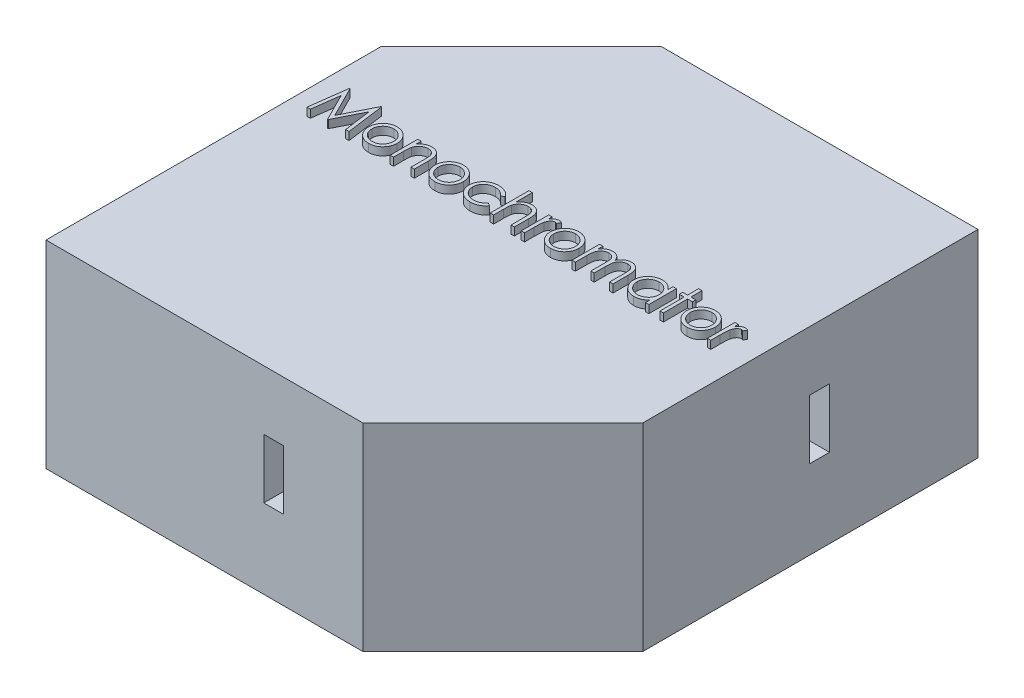
SolidWorks part; units mm, degrees
ref_plane "Front Plane" through (0, 0, 0) normal (0, 0, 1) x (1, 0, 0)
ref_plane "Top Plane" through (0, 0, 0) normal (0, 1, 0) x (1, 0, 0)
ref_plane "Right Plane" through (0, 0, 0) normal (1, 0, 0) x (0, 0, -1)
sketch "Sketch2" plane through (0, 0, 0) normal (0, 1, 0) x (1, 0, 0)
  line L0 (0, 0) -> (80, 0)
  line L1 (80, 0) -> (115.3553, 35.3553)
  line L2 (115.3553, 35.3553) -> (115.3553, 120)
  line L3 (115.3553, 120) -> (35.3553, 120)
  line L4 (35.3553, 120) -> (0, 84.6447)
  line L5 (0, 84.6447) -> (0, 0)
  line L6 (5, 5) -> (77.9289, 5)
  line L7 (77.9289, 5) -> (110.3553, 37.4264)
  line L8 (110.3553, 37.4264) -> (110.3553, 115)
  line L9 (110.3553, 115) -> (37.4264, 115)
  line L10 (37.4264, 115) -> (5, 82.5736)
  line L11 (5, 82.5736) -> (5, 5)
  dimension "D1" = 135
  dimension "D2" = 80
  dimension "D3" = 120
  dimension "D4" = 50
  dimension "D5" = 5
extrude "Boss-Extrude1" add sketch "Sketch2" along normal blind 50
sketch "Sketch3" plane through (0, 0, 0) normal (0, 0, 1) x (1, 0, 0)
  line L0 (0, 0) -> (129.7458, 0) construction
  line L1 (60, 0) -> (60, 56.3218) construction
  line L2 (60, 35) -> (55, 35)
  line L3 (55, 35) -> (55, 20)
  line L4 (55, 20) -> (60, 20)
  line L5 (60, 20) -> (60, 35)
  dimension "D1" = 60
  dimension "D2" = 5
  dimension "D3" = 15
  dimension "D4" = 20
extrude "Cut-Extrude1" cut sketch "Sketch3" against normal blind 50
sketch "Sketch4" plane through (115.3553, 0, 0) normal (1, 0, 0) x (0, 0, -1)
  line L0 (0, 0) -> (137.3061, 0) construction
  line L1 (80, 0) -> (80, 65.5096) construction
  line L2 (77.5, 35) -> (82.5, 35)
  line L3 (77.5, 35) -> (77.5, 20)
  line L4 (77.5, 20) -> (82.5, 20)
  line L5 (82.5, 20) -> (82.5, 35)
  point P8 (80, 35)
  dimension "D1" = 80
  dimension "D2" = 5
  dimension "D3" = 15
  dimension "D4" = 20
extrude "Cut-Extrude2" cut sketch "Sketch4" against normal blind 50
sketch "Sketch5" plane through (0, 0, 0) normal (0, -1, 0) x (1, 0, 0)
  line L0 (0, 0) -> (0, -84.6447)
  line L1 (0, -84.6447) -> (35.3553, -120)
  line L2 (35.3553, -120) -> (115.3553, -120)
  line L3 (115.3553, -120) -> (115.3553, -35.3553)
  line L4 (115.3553, -35.3553) -> (80, 0)
  line L5 (80, 0) -> (0, 0)
extrude "Boss-Extrude2" add sketch "Sketch5" against normal blind 3
sketch "Sketch6" plane through (0, 50, 0) normal (0, 1, 0) x (1, 0, 0)
  line L0 (35.3553, 120) -> (0, 84.6447)
  line L1 (0, 84.6447) -> (0, 0)
  line L2 (0, 0) -> (80, 0)
  line L3 (80, 0) -> (115.3553, 35.3553)
  line L4 (115.3553, 35.3553) -> (115.3553, 120)
  line L5 (115.3553, 120) -> (35.3553, 120)
extrude "Boss-Extrude3" add sketch "Sketch6" against normal blind 3
sketch "Sketch7" plane through (0, 50, 0) normal (0, 1, 0) x (1, 0, 0)
  line L0 (0, 60) -> (115.3553, 60) construction
  line L2 (0, 84.6447) -> (0, 0) construction
  line L3 (115.3553, 35.3553) -> (115.3553, 120) construction
  text T0 "Monochromator" font "Century Gothic" height in points 36
  point P3 (57.6777, 60)
  dimension "D1" = 60
extrude "Boss-Extrude4" add sketch "Sketch7" along normal blind 2
